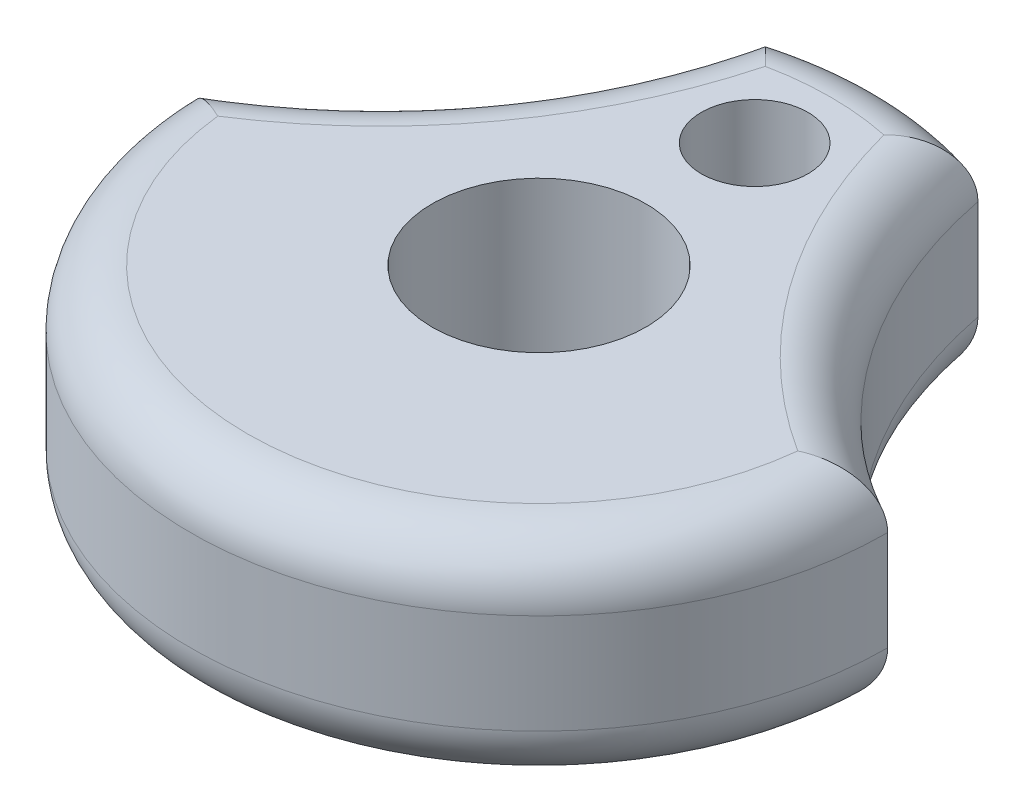
SolidWorks part; units mm, degrees
ref_plane "Front Plane" through (0, 0, 0) normal (0, 0, 1) x (1, 0, 0)
ref_plane "Top Plane" through (0, 0, 0) normal (0, 1, 0) x (1, 0, 0)
ref_plane "Right Plane" through (0, 0, 0) normal (1, 0, 0) x (0, 0, -1)
sketch "Sketch1" plane through (0, 0, 0) normal (0, 1, 0) x (1, 0, 0)
  line L0 (0, -611.492) -> (0, 611.492)
  line L1 (-611.492, 0) -> (611.492, 0)
  arc A0 (188, 581.8749) -> (-188, 581.8749) centre (0, 0) ccw
  arc A1 (611.492, 0) -> (188, 581.8749) centre (1022.3773, 744.0922) cw
  arc A2 (-611.492, 0) -> (-188, 581.8749) centre (-1022.3773, 744.0922) ccw
  circle A3 centre (0, 0) radius 187.5
  circle A4 centre (3.1892, 375) radius 93.5
  arc A5 (-611.492, 0) -> (611.492, 0) centre (0, 0) ccw
  point P9 (0, 0)
  point P11 (335.126, 243.9067)
  point P15 (0, 0)
  point P17 (0, 0)
  point P18 (0, 0)
  point P19 (0, 0)
  dimension "D1" = 188
  dimension "D3" = 375
  dimension "D4" = 187
  dimension "D2" = 850
extrude "Boss-Extrude1" add sketch "Sketch1" along normal blind 375 contours L0 A5 L1 A3 | L1 A5 L0 A3 | A4 L0 A3 L1 A1 A0 | A4 L0 A0 A2 L1 A3
fillet "Fillet1" radius 100 4 edges at (0, 375, -611.492) (0, 375, 611.492) (335.126, 375, -243.9067) (-335.126, 375, -243.9067)
fillet "Fillet2" radius 100 4 edges at (0, 0, -611.492) (-335.126, 0, -243.9067) (335.126, 0, -243.9067) (0, 0, 611.492)
